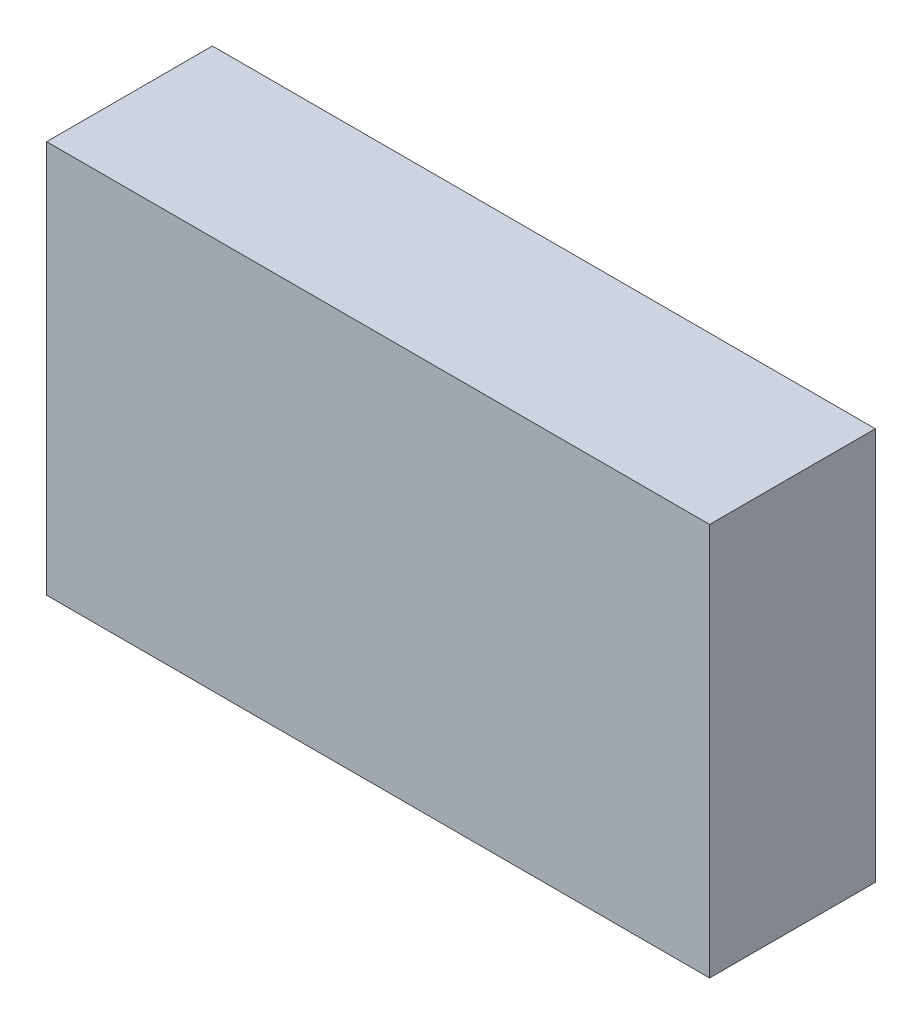
SolidWorks part; units mm, degrees
ref_plane "Front Plane" through (0, 0, 0) normal (0, 0, 1) x (1, 0, 0)
ref_plane "Top Plane" through (0, 0, 0) normal (0, 1, 0) x (1, 0, 0)
ref_plane "Right Plane" through (0, 0, 0) normal (1, 0, 0) x (0, 0, -1)
sketch "Sketch1" plane through (0, 0, 0) normal (0, 0, 1) x (1, 0, 0)
  line L1 (0, 0) -> (40, 0)
  line L2 (0, 0) -> (0, 23.7)
  line L3 (0, 23.7) -> (40, 23.7)
  line L4 (40, 0) -> (40, 23.7)
extrude "Boss-Extrude1" add sketch "Sketch1" along normal blind 10
